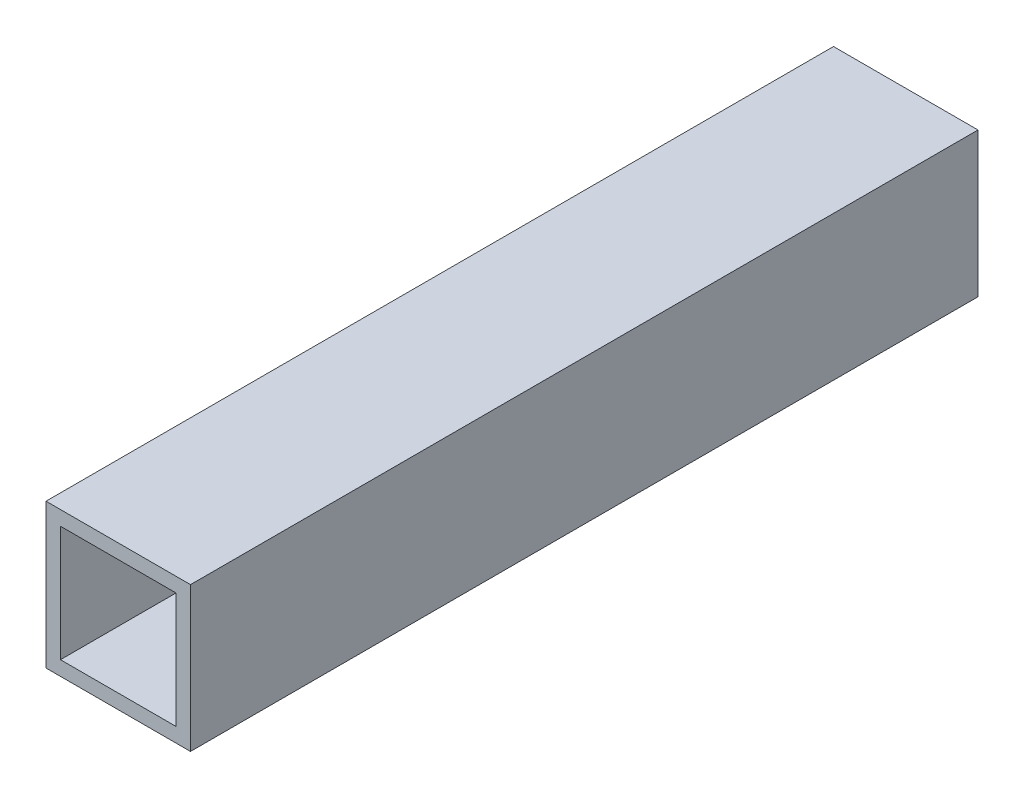
SolidWorks part; units mm, degrees
material "Д16Т ГОСТ 4784-74"
ref_plane "Спереди" through (0, 0, 0) normal (0, 0, 1) x (1, 0, 0)
ref_plane "Сверху" through (0, 0, 0) normal (0, 1, 0) x (1, 0, 0)
ref_plane "Справа" through (0, 0, 0) normal (1, 0, 0) x (0, 0, -1)
sketch "Эскиз1" plane through (0, 0, 0) normal (0, 0, 1) x (1, 0, 0)
  line L1 (0, 0) -> (40, 0)
  line L2 (0, 0) -> (0, 40)
  line L3 (0, 40) -> (40, 40)
  line L4 (40, 0) -> (40, 40)
  dimension "D1" = 40
  dimension "D2" = 40
extrude "Вытянуть-Тонкостенный1" add sketch "Эскиз1" along normal blind 218 thin thin type one direction reverse wall 4
